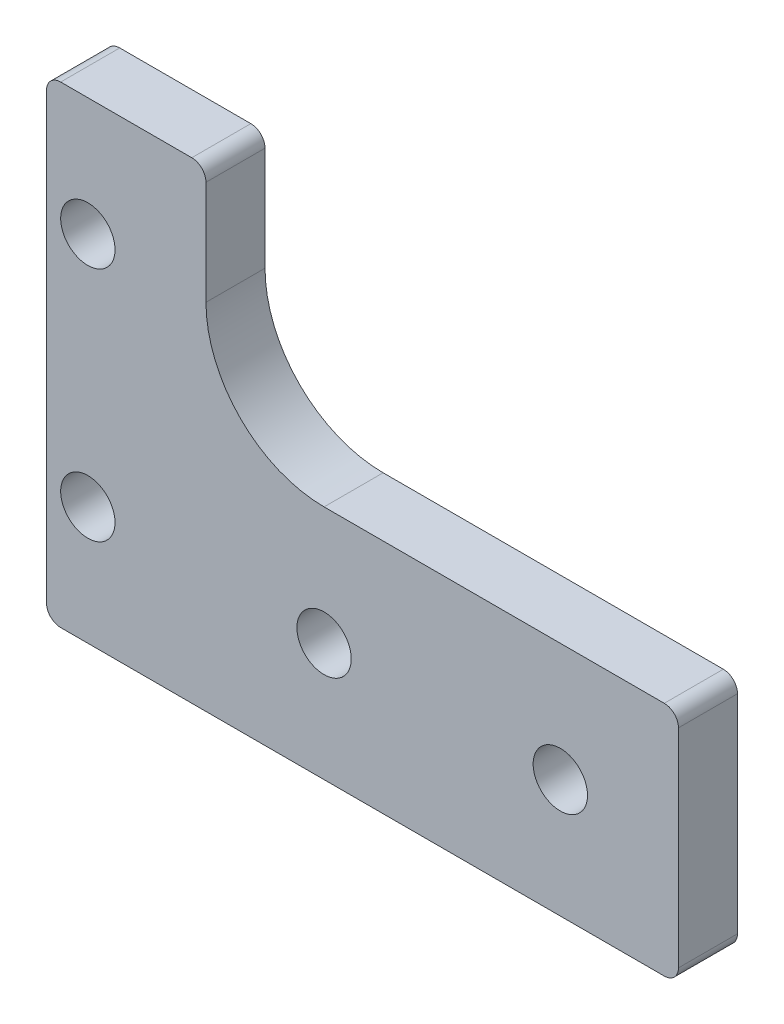
SolidWorks part; units mm, degrees
ref_plane "Front Plane" through (0, 0, 0) normal (0, 0, 1) x (1, 0, 0)
ref_plane "Top Plane" through (0, 0, 0) normal (0, 1, 0) x (1, 0, 0)
ref_plane "Right Plane" through (0, 0, 0) normal (1, 0, 0) x (0, 0, -1)
sketch "Sketch1" plane through (0, 0, 0) normal (0, 0, 1) x (1, 0, 0)
  line L0 (0, 0) -> (0, 50.8)
  line L1 (0, 50.8) -> (25.4, 50.8)
  line L2 (25.4, 50.8) -> (25.4, 25.4)
  line L3 (25.4, 25.4) -> (76.2, 25.4)
  line L4 (76.2, 25.4) -> (76.2, 0)
  line L5 (76.2, 0) -> (0, 0)
  dimension "D1" = 50.8
  dimension "D2" = 25.4
  dimension "3" = 76.2
extrude "Boss-Extrude1" add sketch "Sketch1" along normal blind 6.35
sketch "Sketch2" plane through (0, 0, 6.35) normal (0, 0, 1) x (1, 0, 0)
  line L0 (25.4, 50.8) -> (0, 50.8) construction
  line L1 (25.4, 25.4) -> (25.4, 50.8) construction
  line L2 (0, 0) -> (76.2, 0) construction
  circle A0 centre (12.7, 38.1) radius 2.921
  circle A1 centre (12.7, 12.7) radius 2.921
  circle A2 centre (38.1, 12.7) radius 2.921
  circle A3 centre (63.5, 12.7) radius 2.921
  dimension "D1" = 5.842
  dimension "D2" = 12.7
  dimension "D3" = 12.7
  dimension "D4" = 12.7
  dimension "D5" = 3
extrude "Cut-Extrude1" cut sketch "Sketch2" against normal through all
sketch "Sketch3" plane through (0, 0, 6.35) normal (0, 0, 1) x (1, 0, 0)
  line L0 (25.4, 50.8) -> (0, 50.8) construction
  line L1 (0, 0) -> (8.255, 0)
  line L2 (0, 0) -> (0, 50.8)
  line L3 (0, 50.8) -> (8.255, 50.8)
  line L4 (8.255, 0) -> (8.255, 50.8)
  dimension "D1" = 8.255
extrude "Cut-Extrude2" cut sketch "Sketch3" against normal through all
fillet "Fillet1" radius 12.7 1 edges at (25.4, 25.4, 3.175)
fillet "Fillet2" radius 1.524 5 edges at (76.2, 0, 3.175) (76.2, 25.4, 3.175) (8.255, 0, 3.175) (25.4, 50.8, 3.175) (8.255, 50.8, 3.175)
